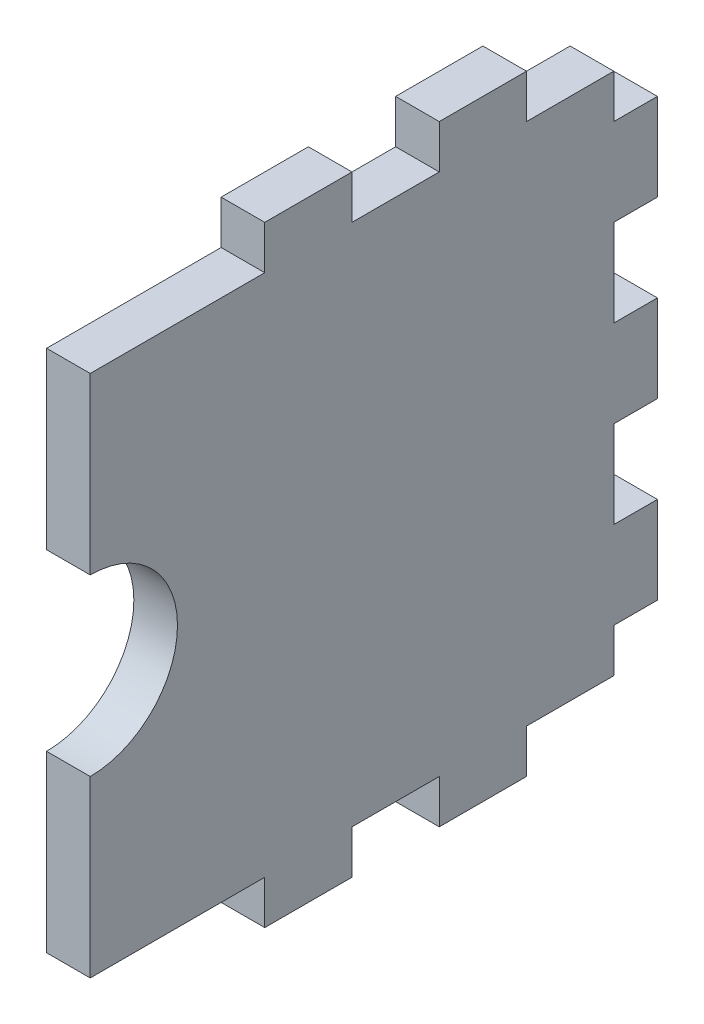
SolidWorks part; units mm, degrees
ref_plane "Front Plane" through (0, 0, 0) normal (1, 0, 0) x (0, 1, 0)
ref_plane "Top Plane" through (0, 0, 0) normal (0, 0, 1) x (0, 1, 0)
ref_plane "Right Plane" through (0, 0, 0) normal (0, 1, 0) x (-1, 0, 0)
sketch "Sketch1" plane through (0, 0, 0) normal (1, 0, 0) x (0, 1, 0)
  line L1 (0, 0) -> (88.9, 0)
  line L2 (0, 0) -> (0, 82.55)
  line L3 (0, 82.55) -> (88.9, 82.55)
  line L4 (88.9, 0) -> (88.9, 82.55)
  dimension "D1" = 88.9
  dimension "D2" = 82.55
extrude "Boss-Extrude1" add sketch "Sketch1" along normal blind 6.35
sketch "Sketch2" plane through (6.35, 0, 0) normal (1, 0, 0) x (0, 1, 0)
  line L5 (50.8, 0) -> (63.5, 0)
  line L23 (50.8, 0) -> (50.8, 6.35)
  line L48 (0, 0) -> (88.9, 0) construction
  line L49 (50.8, 6.35) -> (63.5, 6.35)
  line L50 (25.4, 0) -> (38.1, 0)
  line L51 (0, 0) -> (12.7, 0)
  line L52 (0, 0) -> (0, 6.35)
  line L53 (6.35, 6.35) -> (12.7, 6.35)
  line L54 (12.7, 0) -> (12.7, 6.35)
  line L55 (25.4, 0) -> (25.4, 6.35)
  line L56 (25.4, 6.35) -> (38.1, 6.35)
  line L57 (38.1, 0) -> (38.1, 6.35)
  line L58 (76.2, 0) -> (88.9, 0)
  line L59 (76.2, 0) -> (76.2, 6.35)
  line L60 (76.2, 6.35) -> (82.55, 6.35)
  line L61 (88.9, 0) -> (88.9, 6.35)
  line L62 (63.5, 0) -> (63.5, 6.35)
  line L63 (0, 82.55) -> (0, 0) construction
  line L64 (0, 82.55) -> (6.35, 82.55)
  line L65 (0, 82.55) -> (0, 57.15)
  line L66 (0, 57.15) -> (6.35, 57.15)
  line L67 (6.35, 82.55) -> (6.35, 57.15)
  line L68 (88.9, 82.55) -> (0, 82.55) construction
  line L70 (0, 44.45) -> (6.35, 44.45)
  line L71 (0, 44.45) -> (0, 31.75)
  line L72 (0, 31.75) -> (6.35, 31.75)
  line L73 (6.35, 44.45) -> (6.35, 31.75)
  line L86 (88.9, 6.35) -> (88.9, 19.05)
  line L87 (88.9, 19.05) -> (82.55, 19.05)
  line L88 (82.55, 44.45) -> (82.55, 31.75)
  line L89 (88.9, 31.75) -> (82.55, 31.75)
  line L90 (88.9, 44.45) -> (88.9, 31.75)
  line L91 (88.9, 44.45) -> (82.55, 44.45)
  line L92 (82.55, 82.55) -> (82.55, 57.15)
  line L93 (88.9, 57.15) -> (82.55, 57.15)
  line L94 (88.9, 82.55) -> (88.9, 57.15)
  line L95 (88.9, 82.55) -> (82.55, 82.55)
  line L96 (82.55, 6.35) -> (82.55, 19.05)
  line L98 (6.35, 6.35) -> (6.35, 19.05)
  line L99 (6.35, 19.05) -> (0, 19.05)
  line L100 (0, 6.35) -> (0, 19.05)
  circle A0 centre (44.45, 82.55) radius 12.7
  dimension "D4" = 25.4
  dimension "D5" = 12.7
  dimension "D6" = 6.35
  dimension "D8" = 12.7
  dimension "D9" = 6.35
  dimension "D10" = 0
  dimension "D11" = 12.7
  dimension "D12" = 12.7
  dimension "D14" = 6.35
  dimension "D24" = 12.7
  dimension "D26" = 12.7
  dimension "D31" = 6.35
  dimension "1" = 25.4
extrude "Cut-Extrude2" cut sketch "Sketch2" against normal blind 6.35
